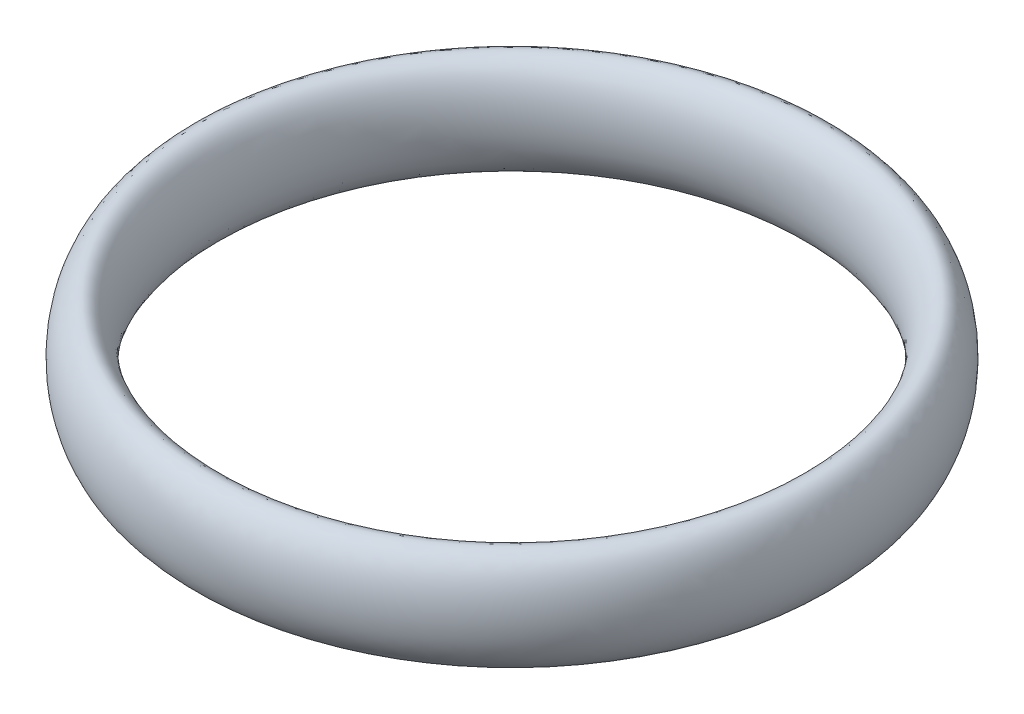
SolidWorks part; units mm, degrees
material "PW20:30:Sc:0:"
ref_plane "Plane1" through (0, 0, 0) normal (0, 0, 1) x (1, 0, 0)
ref_plane "Plane2" through (0, 0, 0) normal (0, 1, 0) x (1, 0, 0)
ref_plane "Plane3" through (0, 0, 0) normal (1, 0, 0) x (0, 0, -1)
sketch "Sketch1" plane through (0, 0, 0) normal (0, 0, 1) x (1, 0, 0)
  line L0 (0, 0) -> (0, 2.54) construction
  line L1 (7.5692, 2.54) -> (7.5692, 0) construction
  ellipse E0 centre (7.5692, 1.27) end of major axis (7.5692, 2.54) minor radius 0.635
  dimension "D1" = 2.54
  dimension "D2" = 1.27
  dimension "D3" = 6.9342
revolve "Body" add sketch "Sketch1" angle 360 about L0
